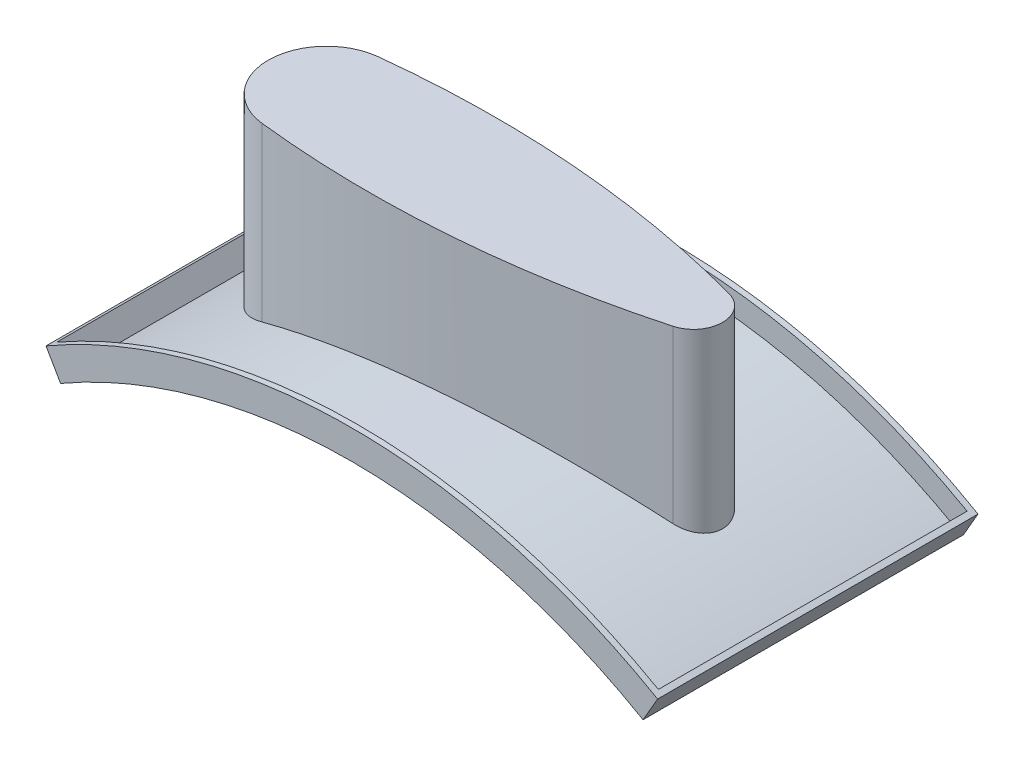
SolidWorks part; units mm, degrees
ref_plane "Front Plane" through (0, 0, 0) normal (0, 0, 1) x (1, 0, 0)
ref_plane "Top Plane" through (0, 0, 0) normal (0, 1, 0) x (1, 0, 0)
ref_plane "Right Plane" through (0, 0, 0) normal (1, 0, 0) x (0, 0, -1)
sketch "Sketch1" plane through (0, 0, 0) normal (0, 0, 1) x (1, 0, 0)
  line L0 (-105, 181.8653) -> (-100, 173.2051)
  line L1 (105, 181.8653) -> (100, 173.2051)
  arc A0 (-100, 173.2051) -> (100, 173.2051) centre (0, 0) cw
  arc A1 (-105, 181.8653) -> (105, 181.8653) centre (0, 0) cw
  point P3 (0, 200)
  dimension "D2" = 200
  dimension "D1" = 200
  dimension "D3" = 10
extrude "Boss-Extrude1" add sketch "Sketch1" against normal blind 110
shell "Shell1" thickness 2
ref_plane "Plane1" through (0, 250, 0) normal (0, 1, 0) x (1, 0, 0)
sketch "Sketch2" plane through (0, 250, 0) normal (0, 1, 0) x (1, 0, 0)
  line L0 (0, 0) -> (0, 110) construction
  line L1 (-105, 0) -> (105, 0) construction
  line L2 (105, 110) -> (-105, 110) construction
  line L3 (-99.263, 55) -> (103.2632, 55) construction
  line L4 (-99.263, 108) -> (-99.263, 2) construction
  line L5 (103.2632, 108) -> (103.2632, 2) construction
  arc A0 (-65.8972, 35.1221) -> (-65.8972, 74.8779) centre (-63.691, 55) cw
  arc A1 (-65.8972, 74.8779) -> (64.9296, 64.6466) centre (-27.2884, -272.986) cw
  arc A2 (-65.8972, 35.1221) -> (64.9296, 45.3534) centre (-27.2884, 382.986) ccw
  arc A3 (64.9296, 64.6466) -> (64.9296, 45.3534) centre (62.2948, 55) cw
  point P15 (72.2948, 55)
  point P16 (0, 75.9485)
  point P19 (58.8594, 68.8831)
  point P20 (64.9296, 74.6466)
  dimension "D1" = 20
  dimension "D2" = 350
  dimension "D3" = 10
extrude "Boss-Extrude2" add sketch "Sketch2" against normal up to surface (59.0509 mm away) contours A2 A3 A1 A0
